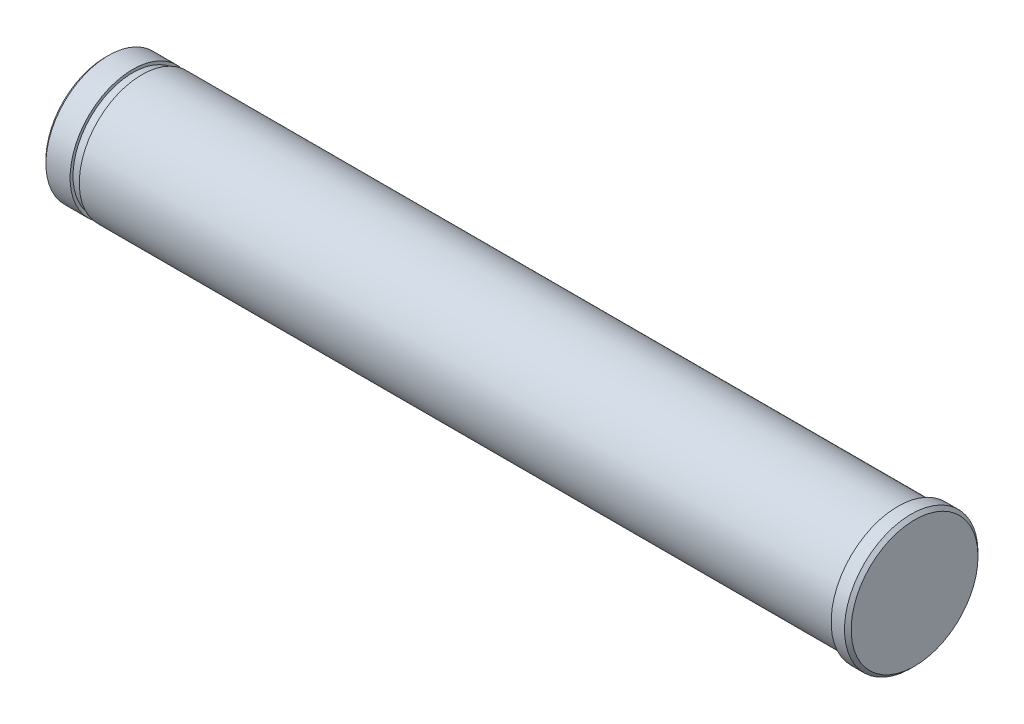
SolidWorks part; units mm, degrees
ref_plane "Front Plane" through (0, 0, 0) normal (0, 0, 1) x (1, 0, 0)
ref_plane "Top Plane" through (0, 0, 0) normal (0, 1, 0) x (1, 0, 0)
ref_plane "Right Plane" through (0, 0, 0) normal (1, 0, 0) x (0, 0, -1)
sketch "Sketch1" plane through (0, 0, 0) normal (1, 0, 0) x (0, 0, -1)
  circle A0 centre (0, 0) radius 7.5
  dimension "D1" = 15
extrude "Boss-Extrude1" add sketch "Sketch1" along normal mid plane 95
sketch "Sketch2" plane through (47.5, 0, 0) normal (1, 0, 0) x (0, 0, -1)
  circle A0 centre (0, 0) radius 8
  dimension "D1" = 16
extrude "Boss-Extrude2" add sketch "Sketch2" along normal blind 2
sketch "Sketch3" plane through (0, 0, 0) normal (0, 1, 0) x (1, 0, 0)
  line L0 (47.5, 7.5) -> (-47.5, 7.5) construction
  line L1 (-44.2, 7.5) -> (-43.1, 7.5)
  line L2 (-44.2, 7.5) -> (-44.2, 7.15)
  line L3 (-44.2, 7.15) -> (-43.1, 7.15)
  line L4 (-43.1, 7.5) -> (-43.1, 7.15)
  line L5 (0, 0) -> (-47.5, 0) construction
  line L6 (-47.5, 7.5) -> (-47.5, -7.5) construction
  line L7 (47.5, 7.5) -> (47.5, -7.5) construction
  point P13 (-44.1301, 6.3268)
  dimension "D1" = 90.6
  dimension "D2" = 14.3
  dimension "D3" = 1.1
revolve "Cut-Revolve1" cut sketch "Sketch3" angle 360 about L5
chamfer "Chamfer1" distance 0.4 angle 45 2 edges at (-47.5, 0, -7.5) (49.5, 0, -8)
